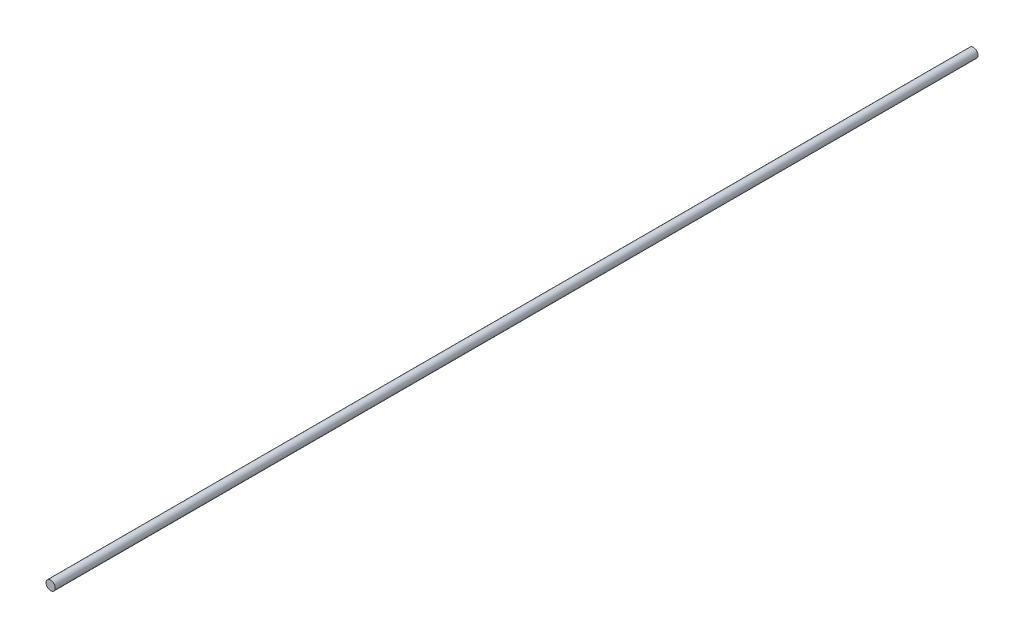
SolidWorks part; units mm, degrees
ref_plane "Ön Düzlem" through (0, 0, 0) normal (0, 0, 1) x (1, 0, 0)
ref_plane "Üst Düzlem" through (0, 0, 0) normal (0, 1, 0) x (1, 0, 0)
ref_plane "Sağ Düzlem" through (0, 0, 0) normal (1, 0, 0) x (0, 0, -1)
sketch "Sketch1" plane through (0, 0, 0) normal (0, 0, 1) x (1, 0, 0)
  circle A0 centre (0, 0) radius 7.5
  dimension "D1" = 15
extrude "Boss-Extrude1" add sketch "Sketch1" along normal blind 1500
